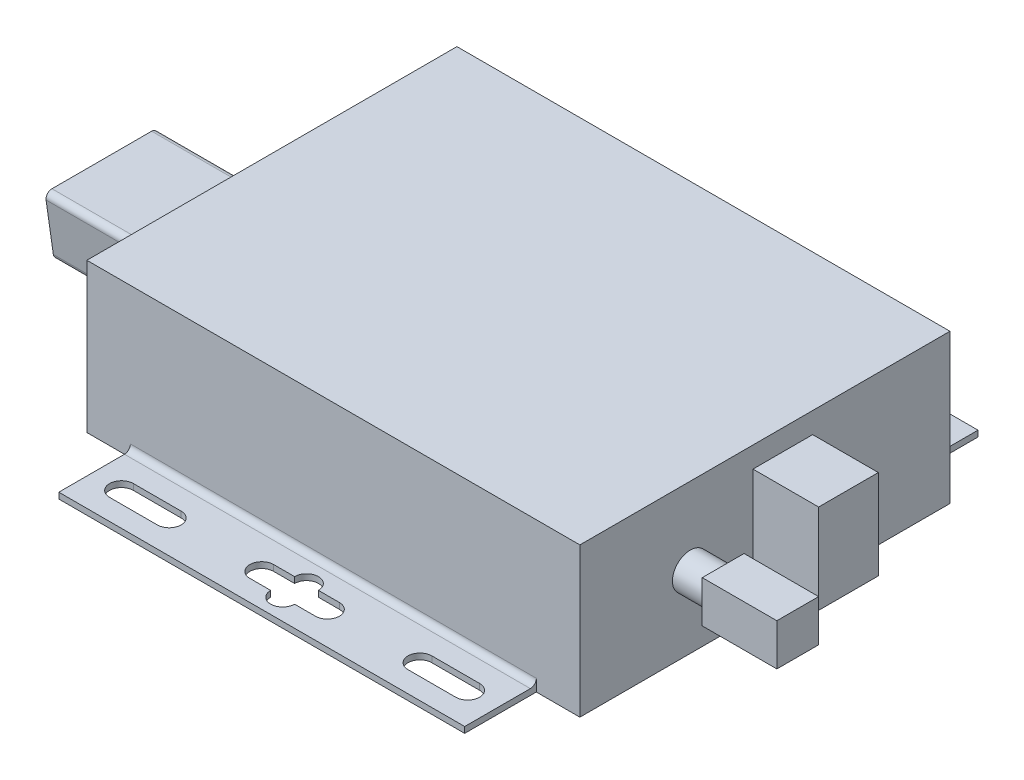
SolidWorks part; units mm, degrees
ref_plane "前视基准面" through (0, 0, 0) normal (0, 0, 1) x (1, 0, 0)
ref_plane "上视基准面" through (0, 0, 0) normal (0, 1, 0) x (1, 0, 0)
ref_plane "右视基准面" through (0, 0, 0) normal (1, 0, 0) x (0, 0, -1)
sketch "草图1" plane through (0, 0, 0) normal (0, 1, 0) x (1, 0, 0)
  line L1 (-41.3, -31) -> (41.3, -31)
  line L2 (-41.3, -31) -> (-41.3, 31)
  line L3 (-41.3, 31) -> (41.3, 31)
  line L4 (41.3, -31) -> (41.3, 31)
  line L5 (-41.3, -31) -> (41.3, 31) construction
  line L6 (-41.3, 31) -> (41.3, -31) construction
  point P0 (0, 0)
  dimension "D1" = 62
  dimension "D2" = 82.6
extrude "凸台-拉伸1" add sketch "草图1" along normal blind 25
sketch "草图2" plane through (0, 0, 0) normal (0, -1, 0) x (1, 0, 0)
  line L0 (-41.3, 31) -> (41.3, 31) construction
  line L1 (-34, 31) -> (34, 31)
  line L2 (-34, 31) -> (-34, 43)
  line L3 (-34, 43) -> (34, 43)
  line L4 (34, 31) -> (34, 43)
  line L5 (-41.3, 0) -> (41.3, 0) construction
  line L6 (41.3, 31) -> (41.3, -31) construction
  line L7 (-29, 37.5) -> (-21, 37.5) construction
  line L8 (-29, 39.5) -> (-21, 39.5)
  line L9 (-29, 35.5) -> (-21, 35.5)
  line L10 (21, 37.5) -> (29, 37.5) construction
  line L11 (21, 39.5) -> (29, 39.5)
  line L12 (21, 35.5) -> (29, 35.5)
  line L13 (-5.5, 37.5) -> (5.5, 37.5) construction
  line L14 (-5.5, 39.5) -> (-2, 39.5)
  line L15 (-5.5, 35.5) -> (-2, 35.5)
  line L16 (0, 39.5) -> (0, 35.5) construction
  line L17 (2, 39.5) -> (5.5, 39.5)
  line L18 (2, 35.5) -> (5.5, 35.5)
  line L19 (0, -39.5) -> (0, -35.5) construction
  line L20 (-5.5, -37.5) -> (5.5, -37.5) construction
  line L21 (2, -35.5) -> (5.5, -35.5)
  line L22 (2, -39.5) -> (5.5, -39.5)
  line L23 (-5.5, -35.5) -> (-2, -35.5)
  line L24 (-5.5, -39.5) -> (-2, -39.5)
  line L25 (34, -31) -> (34, -43)
  line L26 (-34, -43) -> (34, -43)
  line L27 (-34, -31) -> (-34, -43)
  line L28 (-34, -31) -> (34, -31)
  line L29 (21, -37.5) -> (29, -37.5) construction
  line L30 (21, -39.5) -> (29, -39.5)
  line L31 (21, -35.5) -> (29, -35.5)
  line L32 (-29, -37.5) -> (-21, -37.5) construction
  line L33 (-29, -39.5) -> (-21, -39.5)
  line L34 (-29, -35.5) -> (-21, -35.5)
  arc A0 (-29, 39.5) -> (-29, 35.5) centre (-29, 37.5) ccw
  arc A1 (-21, 35.5) -> (-21, 39.5) centre (-21, 37.5) ccw
  arc A2 (21, 39.5) -> (21, 35.5) centre (21, 37.5) ccw
  arc A3 (29, 35.5) -> (29, 39.5) centre (29, 37.5) ccw
  arc A4 (-5.5, 39.5) -> (-5.5, 35.5) centre (-5.5, 37.5) ccw
  arc A5 (5.5, 35.5) -> (5.5, 39.5) centre (5.5, 37.5) ccw
  arc A6 (2, 39.5) -> (-2, 39.5) centre (0, 39.5) ccw
  arc A7 (-2, 35.5) -> (2, 35.5) centre (0, 35.5) ccw
  arc A8 (-2, -35.5) -> (2, -35.5) centre (0, -35.5) cw
  arc A9 (2, -39.5) -> (-2, -39.5) centre (0, -39.5) cw
  arc A10 (5.5, -35.5) -> (5.5, -39.5) centre (5.5, -37.5) cw
  arc A11 (-5.5, -39.5) -> (-5.5, -35.5) centre (-5.5, -37.5) cw
  arc A12 (21, -39.5) -> (21, -35.5) centre (21, -37.5) cw
  arc A13 (29, -35.5) -> (29, -39.5) centre (29, -37.5) cw
  arc A14 (-29, -39.5) -> (-29, -35.5) centre (-29, -37.5) cw
  arc A15 (-21, -35.5) -> (-21, -39.5) centre (-21, -37.5) cw
  point P6 (0, 31)
  point P7 (0, 31)
  point P14 (0, 0)
  point P17 (-25, 37.5)
  point P24 (25, 37.5)
  point P31 (0, 37.5)
  point P37 (0, 37.5)
  point P58 (0, -37.5)
  point P61 (25, -37.5)
  point P68 (-25, -37.5)
  point P73 (0, -31)
  dimension "D9" = 5
  dimension "D13" = 2
  dimension "D14" = 2
  dimension "D15" = 2
  dimension "D16" = 2
  dimension "D17" = 4
  dimension "D1" = 68
  dimension "D2" = 12
  dimension "D3" = 4
  dimension "D4" = 4
  dimension "D5" = 8
  dimension "D6" = 8
  dimension "D7" = 50
  dimension "D8" = 3.5
  dimension "D10" = 11
  dimension "D11" = 4
  dimension "D12" = 25
extrude "凸台-拉伸2" add sketch "草图2" against normal blind 1
fillet "圆角1" radius 1 2 edges at (0, 1, 31) (0, 1, -31)
sketch "草图3" plane through (41.3, 0, 0) normal (1, 0, 0) x (0, 0, -1)
  line L0 (-31, 25) -> (-31, 0) construction
  line L1 (-31, 25) -> (31, 25) construction
  circle A0 centre (-12.5, 12) radius 3
  dimension "D1" = 6
  dimension "D2" = 18.5
  dimension "D3" = 13
extrude "凸台-拉伸3" add sketch "草图3" along normal blind 5.5
sketch "草图4" plane through (41.3, 0, 0) normal (1, 0, 0) x (0, 0, -1)
  line L1 (-2, 6.5) -> (8, 6.5)
  line L2 (-2, 6.5) -> (-2, 21.5)
  line L3 (-2, 21.5) -> (8, 21.5)
  line L4 (8, 6.5) -> (8, 21.5)
  line L5 (-31, 25) -> (31, 25) construction
  line L6 (31, 25) -> (31, 0) construction
  dimension "D1" = 15
  dimension "D2" = 10
  dimension "D3" = 3.5
  dimension "D4" = 33
extrude "凸台-拉伸4" add sketch "草图4" along normal blind 11
sketch "草图5" plane through (-41.3, 0, 0) normal (-1, 0, 0) x (0, 0, 1)
  line L0 (31, 25) -> (31, 0) construction
  line L1 (-7, 19.3) -> (24, 19.3)
  line L2 (-7, 19.3) -> (-7, 6.8)
  line L3 (-7, 6.8) -> (24, 6.8)
  line L4 (24, 19.3) -> (24, 6.8)
  line L5 (-7, 19.3) -> (24, 6.8) construction
  line L6 (-7, 6.8) -> (24, 19.3) construction
  line L7 (-31, 25) -> (31, 25) construction
  point P0 (8.5, 13.05)
  dimension "D1" = 31
  dimension "D2" = 12.5
  dimension "D3" = 7
  dimension "D4" = 5.7
extrude "凸台-拉伸5" add sketch "草图5" along normal blind 5
sketch "草图6" plane through (-46.3, 0, 0) normal (-1, 0, 0) x (0, 0, 1)
  line L0 (-1, 18.3) -> (18, 18.3)
  line L1 (18, 18.3) -> (16.5, 7.8)
  line L2 (16.5, 7.8) -> (0.5, 7.8)
  line L3 (0.5, 7.8) -> (-1, 18.3)
  line L4 (24, 19.3) -> (-7, 19.3) construction
  line L5 (8.5, 19.3) -> (8.5, 6.8) construction
  line L6 (-7, 6.8) -> (24, 6.8) construction
  point P10 (8.5, 18.3)
  dimension "D1" = 19
  dimension "D2" = 16
  dimension "D3" = 10.5
  dimension "D4" = 1
extrude "凸台-拉伸6" add sketch "草图6" along normal blind 15
fillet "圆角2" radius 1 4 edges at (-53.8, 7.8, 16.5) (-53.8, 7.8, 0.5) (-53.8, 18.3, 18) (-53.8, 18.3, -1)
sketch "草图7" plane through (46.8, 0, 0) normal (1, 0, 0) x (0, 0, -1)
  line L1 (-16, 8.5) -> (-9, 8.5)
  line L2 (-16, 8.5) -> (-16, 15.5)
  line L3 (-16, 15.5) -> (-9, 15.5)
  line L4 (-9, 8.5) -> (-9, 15.5)
  line L5 (-16, 8.5) -> (-9, 15.5) construction
  line L6 (-16, 15.5) -> (-9, 8.5) construction
  point P0 (-12.5, 12)
  dimension "D1" = 7
  dimension "D2" = 7
extrude "凸台-拉伸7" add sketch "草图7" along normal blind 12.5
